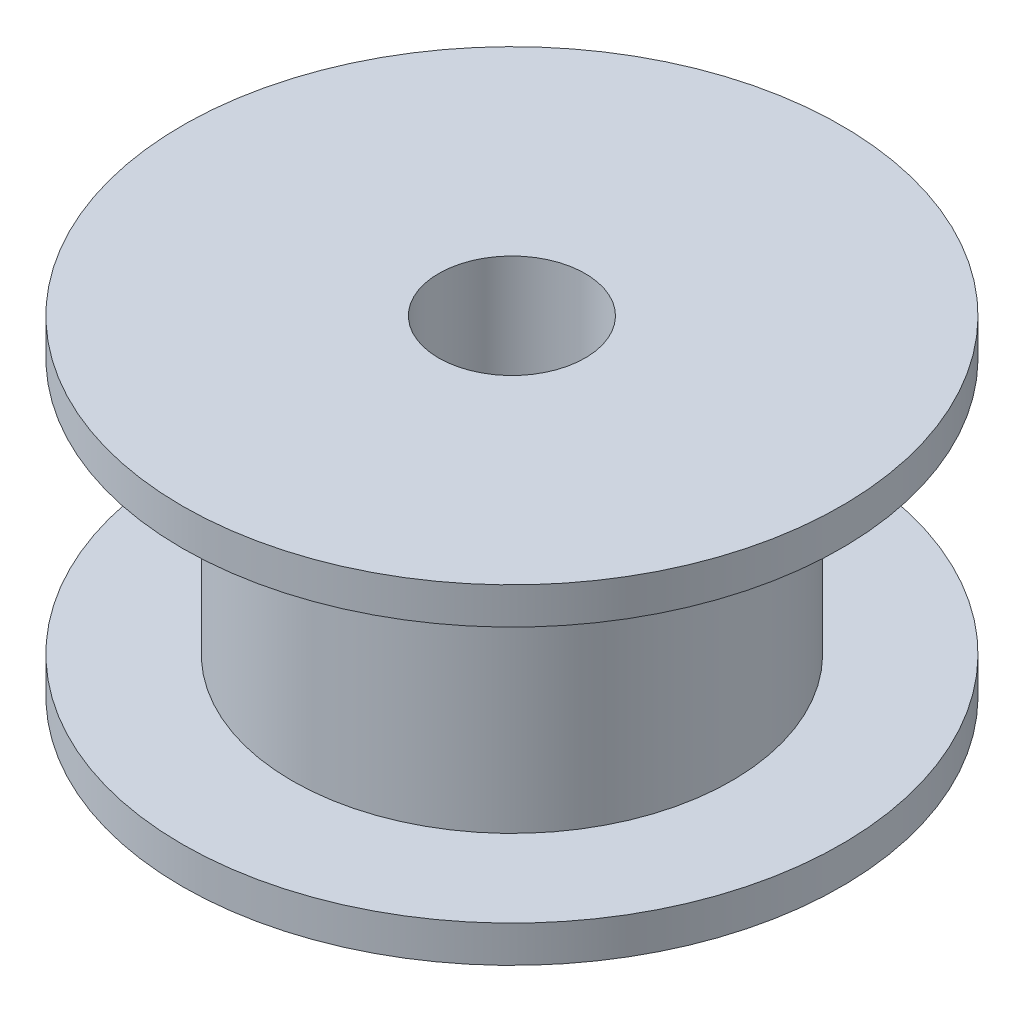
SolidWorks part; units mm, degrees
ref_plane "Front Plane" through (0, 0, 0) normal (0, 0, 1) x (1, 0, 0)
ref_plane "Top Plane" through (0, 0, 0) normal (0, 1, 0) x (1, 0, 0)
ref_plane "Right Plane" through (0, 0, 0) normal (1, 0, 0) x (0, 0, -1)
sketch "Sketch2" plane through (0, 0, 0) normal (0, 1, 0) x (1, 0, 0)
  circle A0 centre (0, 0) radius 9
  dimension "D1" = 18
extrude "Boss-Extrude1" add sketch "Sketch2" along normal blind 1
sketch "Sketch3" plane through (0, 1, 0) normal (0, 1, 0) x (1, 0, 0)
  circle A0 centre (0, 0) radius 6
  dimension "D1" = 12
extrude "Boss-Extrude2" add sketch "Sketch3" along normal blind 7
sketch "Sketch4" plane through (0, 8, 0) normal (0, 1, 0) x (1, 0, 0)
  circle A0 centre (0, 0) radius 9
  dimension "D1" = 18
extrude "Boss-Extrude3" add sketch "Sketch4" along normal blind 1
sketch "Sketch5" plane through (0, 9, 0) normal (0, 1, 0) x (1, 0, 0)
  circle A0 centre (0, 0) radius 2
  dimension "D1" = 4
extrude "Cut-Extrude1" cut sketch "Sketch5" against normal through all
